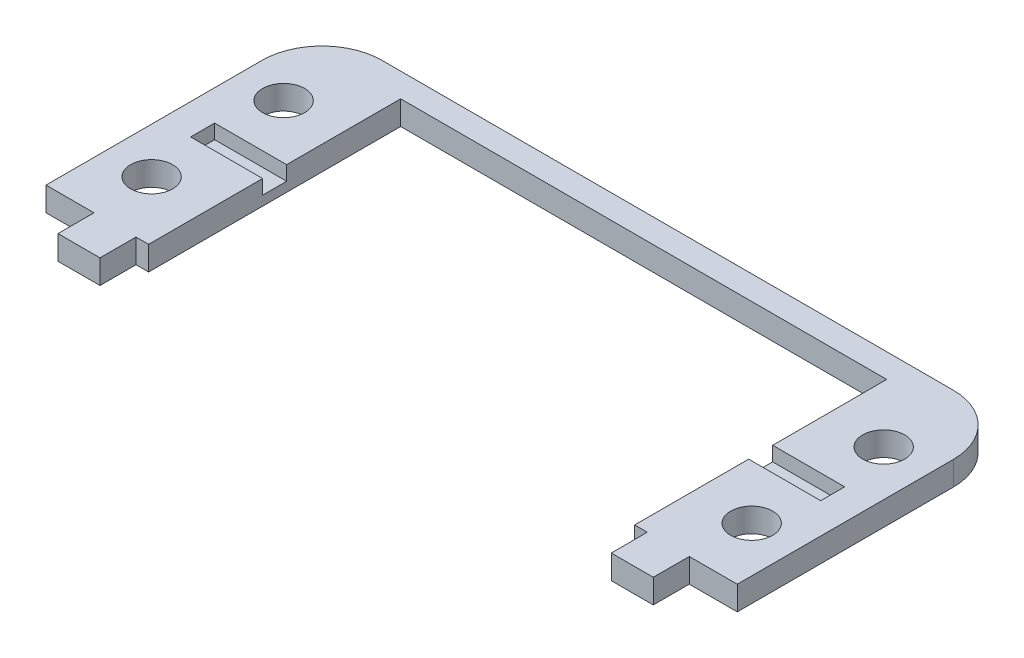
SolidWorks part; units mm, degrees
ref_plane "Front" through (0, 0, 0) normal (0, 0, 1) x (1, 0, 0)
ref_plane "Top" through (0, 0, 0) normal (0, 1, 0) x (1, 0, 0)
ref_plane "Right" through (0, 0, 0) normal (1, 0, 0) x (0, 0, -1)
sketch "Croquis1" plane through (0, 0, 0) normal (0, 1, 0) x (1, 0, 0)
  line L0 (-319.2972, 0) -> (15645.5623, 0) construction
  line L1 (0, -319.2972) -> (0, 15645.5623) construction
  line L2 (-20.25, 0) -> (-20.25, 21)
  line L3 (-20.25, 21) -> (20.25, 21)
  line L4 (20.25, 21) -> (20.25, 0)
  line L5 (-28.8, 0) -> (-28.8, 18)
  line L6 (-23.8, 23) -> (23.8, 23)
  line L7 (28.8, 18) -> (28.8, 0)
  line L8 (-21.3, 0) -> (-20.25, 0)
  line L9 (-28.8, 0) -> (-24.8, 0)
  line L10 (-24.8, 0) -> (-24.8, -3)
  line L11 (-24.8, -3) -> (-21.3, -3)
  line L12 (-21.3, -3) -> (-21.3, 0)
  line L13 (-1020.25, 10.5) -> (48979.75, 10.5) construction
  line L15 (21.3, 0) -> (20.25, 0)
  line L16 (21.3, -3) -> (21.3, 0)
  line L17 (24.8, -3) -> (21.3, -3)
  line L18 (24.8, 0) -> (24.8, -3)
  line L19 (28.8, 0) -> (24.8, 0)
  line L20 (-28.8, 29.55) -> (28.8, 29.55) construction
  line L21 (-28.8, 0) -> (-28.8, 29.55) construction
  line L22 (28.8, 29.55) -> (28.8, 0) construction
  line L23 (6, -319.2972) -> (6, 15645.5623) construction
  line L24 (-6, -319.2972) -> (-6, 15645.5623) construction
  circle A0 centre (-25, 5) radius 1.75
  circle A1 centre (25, 5) radius 1.75
  arc A2 (-28.8, 18) -> (-23.8, 23) centre (-23.8, 18) cw
  arc A3 (28.8, 18) -> (23.8, 23) centre (23.8, 18) ccw
  circle A4 centre (25, 16) radius 1.75
  circle A5 centre (-25, 16) radius 1.75
  point P16 (-20.25, 10.5)
  point P46 (28.8, 23)
  dimension "D5" = 3.5
  dimension "D6" = 4.75
  dimension "D9" = 5
  dimension "D10" = 23
  dimension "D11" = 5.5
  dimension "D12" = 1.05
  dimension "D4" = 5
  dimension "D2" = 40.5
  dimension "D1" = 21
  dimension "D3" = 3
  dimension "D7" = 3.5
  dimension "D8" = 4
extrude "Saliente-Extruir1" add sketch "Croquis1" along normal blind 2
sketch "Croquis2" plane through (0, 2, 0) normal (0, 1, 0) x (1, 0, 0)
  line L0 (-1020.25, 10.5) -> (48979.75, 10.5) construction
  line L1 (-20.25, 0) -> (-20.25, 21) construction
  line L2 (0, -1000) -> (0, 49000) construction
  line L3 (-26.25, 9.5) -> (-20.25, 9.5)
  line L4 (-26.25, 9.5) -> (-26.25, 11.5)
  line L5 (-26.25, 11.5) -> (-20.25, 11.5)
  line L6 (-20.25, 9.5) -> (-20.25, 11.5)
  line L7 (-26.25, 9.5) -> (-20.25, 11.5) construction
  line L8 (-26.25, 11.5) -> (-20.25, 9.5) construction
  line L9 (26.25, 9.5) -> (26.25, 11.5)
  line L10 (26.25, 9.5) -> (20.25, 9.5)
  line L11 (20.25, 9.5) -> (20.25, 11.5)
  line L12 (26.25, 11.5) -> (20.25, 11.5)
  point P1 (-23.25, 10.5)
  point P5 (-20.25, 10.5)
  dimension "D1" = 2
  dimension "D2" = 3
  dimension "D3" = 6
extrude "Cortar-Extruir1" cut sketch "Croquis2" against normal blind 1.2
